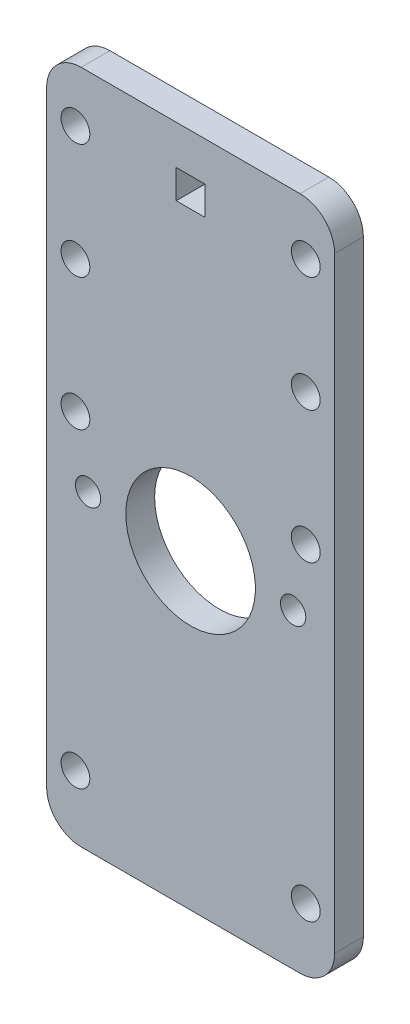
SolidWorks part; units mm, degrees
ref_plane "Front Plane" through (0, 0, 0) normal (0, 0, 1) x (1, 0, 0)
ref_plane "Top Plane" through (0, 0, 0) normal (0, 1, 0) x (1, 0, 0)
ref_plane "Right Plane" through (0, 0, 0) normal (1, 0, 0) x (0, 0, -1)
sketch "Sketch1" plane through (0, 0, 0) normal (0, 0, 1) x (1, 0, 0)
  line L0 (-19.6989, 23.2988) -> (-14.85, 29.7515)
  line L1 (-13.2512, 30.55) -> (13.2512, 30.55)
  line L2 (-20.1, 22.0973) -> (-20.1, -22.0973)
  line L3 (-13.2512, -30.55) -> (13.2512, -30.55)
  line L4 (20.1, 22.0973) -> (20.1, -22.0973)
  line L5 (-20.1, 30.55) -> (20.1, -30.55) construction
  line L6 (-20.1, -30.55) -> (20.1, 30.55) construction
  line L7 (14.85, 29.7515) -> (19.6989, 23.2988)
  line L8 (19.6989, -23.2988) -> (14.85, -29.7515)
  line L9 (-14.85, -29.7515) -> (-19.6989, -23.2988)
  arc A0 (-19.6989, -23.2988) -> (-20.1, -22.0973) centre (-18.1, -22.0973) cw
  arc A1 (-14.85, -29.7515) -> (-13.2512, -30.55) centre (-13.2512, -28.55) ccw
  arc A2 (14.85, -29.7515) -> (13.2512, -30.55) centre (13.2512, -28.55) cw
  arc A3 (19.6989, -23.2988) -> (20.1, -22.0973) centre (18.1, -22.0973) ccw
  arc A4 (19.6989, 23.2988) -> (20.1, 22.0973) centre (18.1, 22.0973) cw
  arc A5 (14.85, 29.7515) -> (13.2512, 30.55) centre (13.2512, 28.55) ccw
  arc A6 (-14.85, 29.7515) -> (-13.2512, 30.55) centre (-13.2512, 28.55) cw
  arc A7 (-19.6989, 23.2988) -> (-20.1, 22.0973) centre (-18.1, 22.0973) ccw
  point P0 (0, 0)
  point P16 (-20.1, -22.765)
  point P19 (-14.25, -30.55)
  point P22 (14.25, -30.55)
  point P25 (20.1, -22.765)
  point P28 (20.1, 22.765)
  point P31 (14.25, 30.55)
  point P34 (-14.25, 30.55)
  point P37 (-20.1, 22.765)
  dimension "D11" = 2
  dimension "D1" = 40.2
  dimension "D2" = 61.1
  dimension "D3" = 5.85
  dimension "D4" = 7.785
  dimension "D5" = 5.85
  dimension "D6" = 7.785
  dimension "D7" = 7.785
  dimension "D8" = 5.85
  dimension "D9" = 5.85
  dimension "D10" = 7.785
extrude "Boss-Extrude1" add sketch "Sketch1" against normal blind 6.35
sketch "Sketch2" plane through (0, 0, -6.35) normal (0, 0, -1) x (-1, 0, 0)
  line L0 (14.85, 29.7515) -> (14.85, -29.7515) construction
  line L1 (-14.85, 29.7515) -> (-14.85, -29.7515) construction
  line L2 (19.6989, 23.2988) -> (-19.6989, 23.2988) construction
  line L3 (20.1, -22.0973) -> (-20.1, -22.0973) construction
  line L4 (0, 30.55) -> (0, -30.55) construction
  line L5 (-13.2512, 30.55) -> (13.2512, 30.55) construction
  line L6 (13.2512, -30.55) -> (-13.2512, -30.55) construction
  circle A0 centre (17.3, 21.9488) radius 1.35
  circle A1 centre (17.3, -0.0512) radius 1.35
  circle A2 centre (17.3, -22.0512) radius 1.35
  circle A3 centre (11, -27.75) radius 1.385
  circle A4 centre (-11, -27.75) radius 1.385
  circle A5 centre (-17.3, -22.0512) radius 1.35
  circle A6 centre (-17.3, -0.0512) radius 1.35
  circle A7 centre (-17.3, 21.9488) radius 1.35
  dimension "D1" = 2.7
  dimension "D5" = 2.77
  dimension "D2" = 22
  dimension "D3" = 22
  dimension "D4" = 17.3
  dimension "D6" = 11
  dimension "D7" = 2.8
extrude "Cut-Extrude1" cut sketch "Sketch2" against normal through all
sketch "Sketch3" plane through (0, 0, -6.35) normal (0, 0, -1) x (-1, 0, 0)
  line L2 (-31.75, 38.2048) -> (31.75, 38.2048)
  line L3 (-31.75, 38.2048) -> (-31.75, -50.6952)
  line L4 (-31.75, -50.6952) -> (31.75, -50.6952)
  line L6 (31.75, 38.2048) -> (31.75, -50.6952)
  line L9 (-19.1605, 23.6188) -> (19.1605, 23.6188)
  line L10 (-19.1605, 23.6188) -> (-19.1605, -23.6188)
  line L11 (-19.1605, -23.6188) -> (19.1605, -23.6188)
  line L12 (19.1605, 23.6188) -> (19.1605, -23.6188)
  circle A0 centre (17.3, 21.9488) radius 1.35 construction
  point P0 (0, 0)
  point P6 (0, 0)
  dimension "D4" = 16.256
  dimension "D1" = 63.5
  dimension "D2" = 88.9
  dimension "D3" = 31.75
extrude "Boss-Extrude2" add sketch "Sketch3" against normal blind 6.35
sketch "Sketch5" plane through (0, 0, 0) normal (0, 0, 1) x (1, 0, 0)
  line L1 (-13.97, 30.9488) -> (13.97, 30.9488)
  line L2 (-13.97, 30.9488) -> (-13.97, -24.9312)
  line L3 (-13.97, -24.9312) -> (13.97, -24.9312)
  line L4 (13.97, 30.9488) -> (13.97, -24.9312)
  circle A0 centre (17.3, 21.9488) radius 1.35 construction
  dimension "D1" = 27.94
  dimension "D2" = 55.88
  dimension "D3" = 9
extrude "Cut-Extrude3" cut sketch "Sketch5" against normal through all
sketch "Sketch6" plane through (0, 0, -6.35) normal (0, 0, -1) x (-1, 0, 0)
  line L0 (-13.97, 30.9488) -> (13.97, 30.9488) construction
  line L1 (31.75, 38.2048) -> (-31.75, 38.2048) construction
  circle A0 centre (25.4, 31.8548) radius 3.175
  circle A1 centre (-25.4, 31.8548) radius 3.175
  circle A2 centre (-25.4, -36.7252) radius 3.175
  circle A3 centre (25.4, -36.7252) radius 3.175
  point P4 (0, 30.9488)
  dimension "D1" = 25.4
  dimension "D2" = 6.35
  dimension "D5" = 50.8
  dimension "D3" = 2
  dimension "D4" = 2
extrude "Cut-Extrude4" cut sketch "Sketch6" against normal through all
sketch "Sketch7" plane through (0, 0, -6.35) normal (0, 0, -1) x (-1, 0, 0)
  line L1 (-20.8625, 32.0966) -> (20.8625, 32.0966)
  line L2 (-20.8625, 32.0966) -> (-20.8625, -25.7617)
  line L3 (-20.8625, -25.7617) -> (20.8625, -25.7617)
  line L4 (20.8625, 32.0966) -> (20.8625, -25.7617)
  line L5 (-20.8625, 32.0966) -> (20.8625, -25.7617) construction
  line L6 (-20.8625, -25.7617) -> (20.8625, 32.0966) construction
  point P0 (0, 3.1674)
extrude "Boss-Extrude3" add sketch "Sketch7" against normal blind 6.35
sketch "Sketch8" plane through (0, 0, -6.35) normal (0, 0, -1) x (-1, 0, 0)
  line L0 (31.75, 38.2048) -> (-31.75, 38.2048) construction
  circle A0 centre (0, 17.8848) radius 14.2875
  dimension "D1" = 20.32
extrude "Cut-Extrude5" cut sketch "Sketch8" against normal blind 6.35
sketch "Sketch10" plane through (0, 0, -6.35) normal (0, 0, -1) x (-1, 0, 0)
  line L1 (-31.75, 38.2048) -> (31.75, 38.2048)
  line L2 (-31.75, 38.2048) -> (-31.75, 98.2048)
  line L3 (-31.75, 98.2048) -> (31.75, 98.2048)
  line L4 (31.75, 38.2048) -> (31.75, 98.2048)
  line L5 (-3.175, 89.5548) -> (3.175, 89.5548)
  line L6 (-3.175, 89.5548) -> (-3.175, 83.2048)
  line L7 (-3.175, 83.2048) -> (3.175, 83.2048)
  line L8 (3.175, 89.5548) -> (3.175, 83.2048)
  line L9 (-3.175, 89.5548) -> (3.175, 83.2048) construction
  line L10 (-3.175, 83.2048) -> (3.175, 89.5548) construction
  circle A0 centre (-25.4, 86.3798) radius 3.175
  circle A1 centre (-25.4, 60.9798) radius 3.175
  circle A2 centre (25.4, 60.9798) radius 3.175
  circle A3 centre (25.4, 86.3798) radius 3.175
  point P5 (0, 86.3798)
  dimension "D3" = 2
  dimension "D1" = 60
  dimension "D2" = 45
extrude "Boss-Extrude4" add sketch "Sketch10" against normal blind 6.35
fillet "Fillet1" radius 7.62 4 edges at (-31.75, -50.6952, -3.175) (31.75, -50.6952, -3.175) (-31.75, 98.2048, -3.175) (31.75, 98.2048, -3.175)
sketch "Sketch11" plane through (0, 0, 0) normal (0, 0, 1) x (1, 0, 0)
  circle A0 centre (-22.61, 17.8848) radius 2.794
  circle A1 centre (0, 17.8848) radius 14.2875 construction
  circle A2 centre (22.61, 17.8848) radius 2.794
  dimension "D1" = 22.61
  dimension "D2" = 22.61
extrude "Cut-Extrude6" cut sketch "Sketch11" against normal through all
